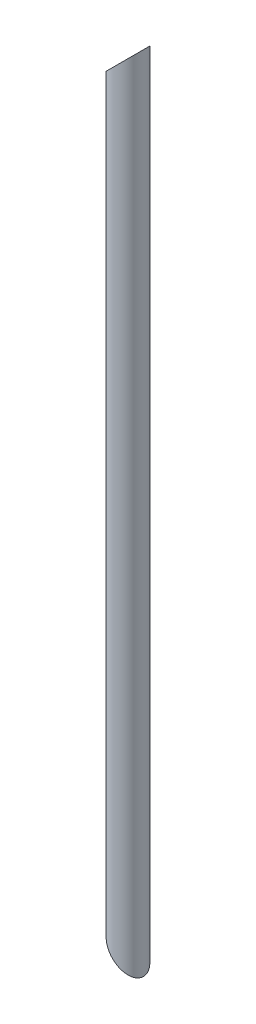
SolidWorks part; units mm, degrees
ref_plane "Plano frontal" through (0, 0, 0) normal (0, 0, 1) x (1, 0, 0)
ref_plane "Plano superior" through (0, 0, 0) normal (0, 1, 0) x (1, 0, 0)
ref_plane "Plano direito" through (0, 0, 0) normal (1, 0, 0) x (0, 0, -1)
sketch "Esboço2" plane through (0, 0, 0) normal (0, 0, 1) x (1, 0, 0)
  line L0 (0, 0) -> (0, 1650) construction
  line L1 (31.75, 0) -> (31.75, 1650)
  line L2 (31.75, 1650) -> (0, 1650)
  line L3 (31.75, 0) -> (0, 0)
  line L4 (0, 0) -> (0, 1650)
  dimension "D1" = 31.75
  dimension "D2" = 1650
revolve "Revolução2" add sketch "Esboço2" angle 360 about L0
sketch "Esboço3" plane through (0, 0, 0) normal (0, 0, 1) x (1, 0, 0)
  line L0 (-31.75, 1650) -> (31.75, 1650)
  line L1 (31.75, 1650) -> (-31.75, 1586.5)
  line L2 (-31.75, 1650) -> (-31.75, 0) construction
  line L3 (-31.75, 1586.5) -> (-31.75, 1650)
  line L4 (31.75, 0) -> (-31.75, 63.5)
  line L8 (-31.75, 63.5) -> (-31.75, 0)
  line L9 (-31.75, 0) -> (31.75, 0)
extrude "Corte-extrusão1" cut sketch "Esboço3" against normal through all both and the other way through all
sketch "Esboço9" plane through (0, 0, 0) normal (0, 1, 0) x (1, 0, 0)
  circle A0 centre (0, 0) radius 30.75
  dimension "D1" = 61.5
extrude "Corte-extrusão6" cut sketch "Esboço9" along normal through all
